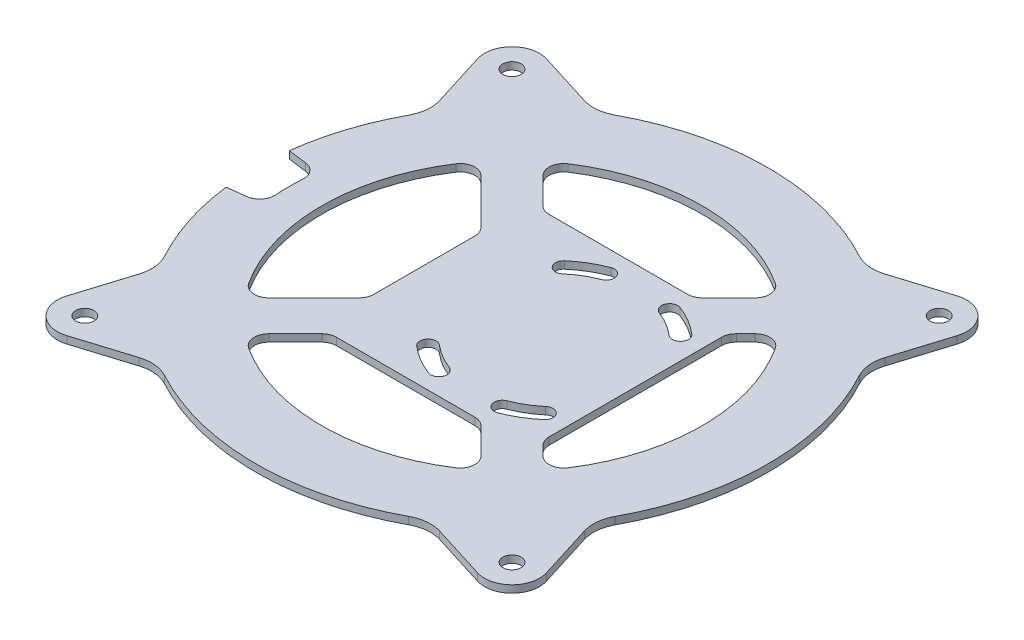
SolidWorks part; units mm, degrees
ref_plane "前视基准面" through (0, 0, 0) normal (0, 0, 1) x (1, 0, 0)
ref_plane "上视基准面" through (0, 0, 0) normal (0, 1, 0) x (1, 0, 0)
ref_plane "右视基准面" through (0, 0, 0) normal (1, 0, 0) x (0, 0, -1)
sketch "草图2" plane through (0, 0, 0) normal (0, 1, 0) x (1, 0, 0)
  line L0 (5.77, 10.5) -> (5.77, -10.5) construction
  line L1 (-4.23, -4.23) -> (4.23, -4.23)
  line L2 (-4.23, -4.23) -> (-4.23, 4.23)
  line L3 (-4.23, 4.23) -> (4.23, 4.23)
  line L4 (4.23, -4.23) -> (4.23, 4.23)
  line L5 (-4.23, -4.23) -> (4.23, 4.23) construction
  line L6 (-4.23, 4.23) -> (4.23, -4.23) construction
  line L7 (14.03, -12.61) -> (-9.97, -12.61)
  line L8 (14.03, -12.61) -> (14.03, 12.61)
  line L9 (14.03, 12.61) -> (-9.97, 12.61)
  line L10 (-9.97, -12.61) -> (-9.97, 12.61)
  line L11 (14.03, -12.61) -> (-9.97, 12.61) construction
  line L12 (14.03, 12.61) -> (-9.97, -12.61) construction
  line L13 (-0.48, -10.5) -> (12.02, -10.5) construction
  line L14 (-0.48, -10.5) -> (-0.48, 10.5) construction
  line L15 (-0.48, 10.5) -> (12.02, 10.5) construction
  line L16 (12.02, -10.5) -> (12.02, 10.5) construction
  line L17 (-0.48, -10.5) -> (12.02, 10.5) construction
  line L18 (-0.48, 10.5) -> (12.02, -10.5) construction
  line L19 (12.02, 0) -> (-0.48, 0) construction
  circle A0 centre (0, 0) radius 3.5427
  circle A1 centre (-0.48, 10.5) radius 1.05
  circle A2 centre (12.02, 10.5) radius 1.05
  circle A3 centre (12.02, -10.5) radius 1.05
  circle A4 centre (-0.48, -10.5) radius 1.05
  point P7 (2.03, 0)
  point P13 (5.77, 0)
  dimension "D1" = 7.0854
  dimension "D7" = 2.1
  dimension "D8" = 10.4
  dimension "D9" = 18.9
  dimension "D2" = 8.46
  dimension "D3" = 8.46
  dimension "D4" = 24
  dimension "D5" = 25.22
  dimension "D6" = 5.74
  dimension "D10" = 8.44
sketch "草图1" plane through (0, 0, 0) normal (0, 1, 0) x (1, 0, 0)
  line L0 (12.02, 0) -> (-0.48, 0) construction
  line L1 (5.77, 10.5) -> (5.77, -10.5) construction
  line L2 (12.02, 0) -> (-0.48, 0) construction
  line L3 (5.77, 10.5) -> (5.77, -10.5) construction
  line L4 (0, 0) -> (29.1682, 29.1682) construction
  line L5 (2.03, 0) -> (35, 0) construction
  line L6 (32.7482, 28.052) -> (30.4032, 20.5305)
  line L7 (28.052, 32.7482) -> (20.5305, 30.4032)
  line L8 (28.052, -32.7482) -> (20.5305, -30.4032)
  line L9 (32.7482, -28.052) -> (30.4032, -20.5305)
  line L10 (-32.7482, -28.052) -> (-30.4032, -20.5305)
  line L11 (-28.052, -32.7482) -> (-20.5305, -30.4032)
  line L12 (-28.052, 32.7482) -> (-20.5305, 30.4032)
  line L13 (-32.7482, 28.052) -> (-30.4032, 20.5305)
  line L14 (18.7195, -14.4769) -> (17.4341, -13.1915)
  line L15 (-10.8689, -15.1116) -> (-14.4769, -18.7195)
  line L16 (-9.97, -12.61) -> (-9.97, 12.61) construction
  line L17 (10.8689, -15.1116) -> (14.4769, -18.7195)
  line L18 (16.8484, -11.7773) -> (16.8484, 11.7773)
  line L20 (-11.97, -6.8989) -> (-11.97, 6.8989)
  line L21 (9.4547, 14.5258) -> (-9.4547, 14.5258)
  line L22 (18.7195, 14.4769) -> (17.4341, 13.1915)
  line L23 (10.8689, 15.1116) -> (14.4769, 18.7195)
  line L24 (0, 0) -> (-29.1682, 29.1682) construction
  line L25 (-10.8689, 15.1116) -> (-14.4769, 18.7195)
  line L26 (-12.5558, 8.3131) -> (-18.7195, 14.4769)
  line L27 (0, 0) -> (-26, 0) construction
  line L28 (-0.48, 10.5) -> (12.02, -10.5) construction
  line L29 (5.77, 0) -> (-2.9266, 10.0883) construction
  line L30 (-0.48, 10.5) -> (12.02, -10.5) construction
  line L31 (9.4547, -14.5258) -> (-9.4547, -14.5258)
  line L32 (-12.5558, -8.3131) -> (-18.7195, -14.4769)
  line L33 (0, 0) -> (-34.7329, 4.3159) construction
  line L34 (-32.1908, 4) -> (-34.7329, 4.3159)
  line L35 (-34.7329, 4.3159) -> (-25.8016, 3.2061) construction
  line L36 (-32.1908, -4) -> (-34.7329, -4.3159)
  circle A0 centre (0, 0) radius 34 construction
  circle A1 centre (0, 0) radius 27 construction
  circle A2 centre (-0.48, 10.5) radius 1.1 construction
  circle A6 centre (0, 0) radius 35 construction
  circle A7 centre (29.1682, 29.1682) radius 1.25
  arc A8 (28.052, 32.7482) -> (32.7482, 28.052) centre (29.1682, 29.1682) cw
  arc A9 (30.7795, 16.662) -> (35, 0) centre (0, 0) cw
  arc A10 (30.7795, 16.662) -> (30.4032, 20.5305) centre (35.1766, 19.0423) cw
  arc A11 (16.662, 30.7795) -> (0, 35) centre (0, 0) ccw
  arc A12 (16.662, 30.7795) -> (20.5305, 30.4032) centre (19.0423, 35.1766) ccw
  arc A13 (16.662, -30.7795) -> (0, -35) centre (0, 0) cw
  circle A14 centre (29.1682, -29.1682) radius 1.25
  arc A15 (32.7482, -28.052) -> (28.052, -32.7482) centre (29.1682, -29.1682) cw
  arc A16 (16.662, -30.7795) -> (20.5305, -30.4032) centre (19.0423, -35.1766) cw
  arc A17 (30.7795, -16.662) -> (35, 0) centre (0, 0) ccw
  arc A18 (30.7795, -16.662) -> (30.4032, -20.5305) centre (35.1766, -19.0423) ccw
  arc A19 (-30.7795, -16.662) -> (-35, 0) centre (0, 0) cw
  circle A20 centre (-29.1682, -29.1682) radius 1.25
  arc A21 (-28.052, -32.7482) -> (-32.7482, -28.052) centre (-29.1682, -29.1682) cw
  arc A22 (-30.7795, -16.662) -> (-30.4032, -20.5305) centre (-35.1766, -19.0423) cw
  arc A23 (-16.662, -30.7795) -> (0, -35) centre (0, 0) ccw
  arc A24 (-16.662, -30.7795) -> (-20.5305, -30.4032) centre (-19.0423, -35.1766) ccw
  arc A25 (-16.662, 30.7795) -> (0, 35) centre (0, 0) cw
  circle A26 centre (-29.1682, 29.1682) radius 1.25
  arc A27 (-32.7482, 28.052) -> (-28.052, 32.7482) centre (-29.1682, 29.1682) cw
  arc A28 (-16.662, 30.7795) -> (-20.5305, 30.4032) centre (-19.0423, 35.1766) cw
  arc A29 (-30.7795, 16.662) -> (-35, 0) centre (0, 0) ccw
  arc A30 (-30.7795, 16.662) -> (-30.4032, 20.5305) centre (-35.1766, 19.0423) ccw
  circle A31 centre (0, 0) radius 26 construction
  arc A32 (21.8115, -14.1512) -> (21.8115, 14.1512) centre (0, 0) ccw
  arc A33 (-14.1512, 21.8115) -> (14.1512, 21.8115) centre (0, 0) cw
  arc A34 (-21.8115, 14.1512) -> (-21.8115, -14.1512) centre (0, 0) ccw
  arc A35 (1.0483, 12.4543) -> (-2.9266, 10.0883) centre (5.77, 0) ccw
  arc A36 (1.8282, 10.3972) -> (-1.4901, 8.422) centre (5.77, 0) ccw
  arc A37 (-2.9266, 10.0883) -> (-1.4901, 8.422) centre (-2.2084, 9.2552) ccw
  arc A38 (1.0483, 12.4543) -> (1.8282, 10.3972) centre (1.4383, 11.4258) cw
  arc A39 (10.4917, 12.4543) -> (9.7118, 10.3972) centre (10.1017, 11.4258) ccw
  arc A40 (10.4917, 12.4543) -> (14.4666, 10.0883) centre (5.77, 0) cw
  arc A41 (14.4666, 10.0883) -> (13.0301, 8.422) centre (13.7484, 9.2552) cw
  arc A42 (9.7118, 10.3972) -> (13.0301, 8.422) centre (5.77, 0) cw
  arc A43 (1.0483, -12.4543) -> (1.8282, -10.3972) centre (1.4383, -11.4258) ccw
  arc A44 (1.0483, -12.4543) -> (-2.9266, -10.0883) centre (5.77, 0) cw
  arc A45 (-2.9266, -10.0883) -> (-1.4901, -8.422) centre (-2.2084, -9.2552) cw
  arc A46 (1.8282, -10.3972) -> (-1.4901, -8.422) centre (5.77, 0) cw
  arc A47 (10.4917, -12.4543) -> (14.4666, -10.0883) centre (5.77, 0) ccw
  arc A48 (14.4666, -10.0883) -> (13.0301, -8.422) centre (13.7484, -9.2552) ccw
  arc A49 (9.7118, -10.3972) -> (13.0301, -8.422) centre (5.77, 0) ccw
  arc A50 (10.4917, -12.4543) -> (9.7118, -10.3972) centre (10.1017, -11.4258) cw
  arc A51 (-21.8115, 14.1512) -> (-18.7195, 14.4769) centre (-20.1337, 13.0627) cw
  arc A52 (-14.1512, 21.8115) -> (-14.4769, 18.7195) centre (-13.0627, 20.1337) ccw
  arc A53 (18.7195, 14.4769) -> (21.8115, 14.1512) centre (20.1337, 13.0627) cw
  arc A54 (14.1512, 21.8115) -> (14.4769, 18.7195) centre (13.0627, 20.1337) cw
  arc A55 (17.4341, 13.1915) -> (16.8484, 11.7773) centre (18.8484, 11.7773) ccw
  arc A56 (10.8689, 15.1116) -> (9.4547, 14.5258) centre (9.4547, 16.5258) cw
  arc A57 (-10.8689, 15.1116) -> (-9.4547, 14.5258) centre (-9.4547, 16.5258) ccw
  arc A58 (-12.5558, 8.3131) -> (-11.97, 6.8989) centre (-13.97, 6.8989) cw
  arc A59 (17.4341, -13.1915) -> (16.8484, -11.7773) centre (18.8484, -11.7773) cw
  arc A60 (18.7195, -14.4769) -> (21.8115, -14.1512) centre (20.1337, -13.0627) ccw
  arc A61 (-14.1512, -21.8115) -> (-14.4769, -18.7195) centre (-13.0627, -20.1337) cw
  arc A62 (-14.1512, -21.8115) -> (14.1512, -21.8115) centre (0, 0) ccw
  arc A63 (14.1512, -21.8115) -> (14.4769, -18.7195) centre (13.0627, -20.1337) ccw
  arc A64 (10.8689, -15.1116) -> (9.4547, -14.5258) centre (9.4547, -16.5258) ccw
  arc A65 (-10.8689, -15.1116) -> (-9.4547, -14.5258) centre (-9.4547, -16.5258) cw
  arc A66 (-12.5558, -8.3131) -> (-11.97, -6.8989) centre (-13.97, -6.8989) ccw
  arc A67 (-21.8115, -14.1512) -> (-18.7195, -14.4769) centre (-20.1337, -13.0627) ccw
  arc A68 (-30.4413, -1.8912) -> (-30.4413, 1.8912) centre (0, 0) cw
  arc A69 (-30.4413, 1.8912) -> (-32.1908, 4) centre (-32.4375, 2.0153) ccw
  arc A70 (-30.4413, -1.8912) -> (-32.1908, -4) centre (-32.4375, -2.0153) cw
  point P12 (-1.0426, 11.4452)
  point P30 (29.7504, 18.4367)
  point P68 (-16.1407, 20.3833)
  point P72 (0, 0)
  point P93 (-30.2672, 3.761)
  point P97 (-30.2672, 3.761)
  point P126 (-20.3833, 16.1407)
  point P139 (16.8484, 0)
  point P156 (-11.97, 0)
  dimension "D1" = 68
  dimension "D2" = 7
  dimension "D3" = 2.2
  dimension "D4" = 1
  dimension "D5" = 2.5
  dimension "D7" = 5
  dimension "D8" = 2.5
  dimension "D10" = 5
  dimension "D12" = 1
  dimension "D21" = 2
  dimension "D6" = 2
  dimension "D9" = 8
  dimension "D13" = 3
  dimension "D14" = 3
  dimension "D15" = 3
  dimension "D16" = 3
  dimension "D17" = 10
  dimension "D18" = 2
  dimension "D19" = 2
  dimension "D20" = 2
  dimension "D22" = 8
  dimension "D11" = 4
extrude "凸台-拉伸1" add sketch "草图1" along normal blind 1 contours A30 A29 A19 A22 L10 A21 L11 A24 A23 A13 A16 L8 A15 L9 A18 A17 A9 A10 L6 A8 L7 A12 A11 A25 A28 L12 A27 L13 A67 A34 A51 L26 A58 L20 A66 L32 A60 L14 A59 L18 A55 L22 A53 A32 A57 L25 A52 A33
